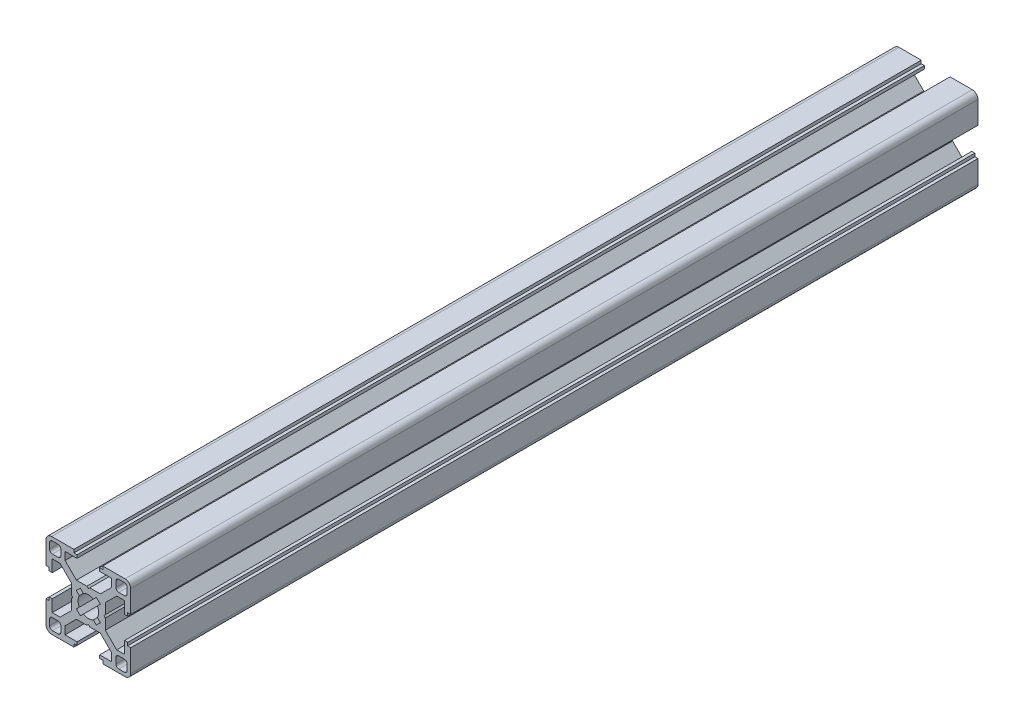
SolidWorks part; units mm, degrees
material "1060 Alloy"
ref_plane "Front Plane" through (0, 0, 0) normal (0, 0, 1) x (1, 0, 0)
ref_plane "Top Plane" through (0, 0, 0) normal (0, 1, 0) x (1, 0, 0)
ref_plane "Right Plane" through (0, 0, 0) normal (1, 0, 0) x (0, 0, -1)
sketch "Sketch1" plane through (0, 0, 0) normal (0, 0, 1) x (1, 0, 0)
  line L0 (5.1, 15) -> (13, 15)
  line L1 (15, -15) -> (-15, -15) construction
  line L2 (15, -15) -> (15, 15) construction
  line L3 (15, 15) -> (-15, 15) construction
  line L4 (-15, -15) -> (-15, 15) construction
  line L5 (15, -15) -> (-15, 15) construction
  line L6 (15, 15) -> (-15, -15) construction
  line L7 (-6, -6) -> (6, -6)
  line L8 (-6, -6) -> (-6, 6)
  line L9 (-6, 6) -> (4.2322, 6)
  line L10 (6, -6) -> (6, 4.2322)
  line L11 (-6, -6) -> (5.7915, 5.7915) construction
  line L12 (-6, 6) -> (6, -6) construction
  line L13 (15, 13) -> (15, 5.1)
  line L14 (15, 5.1) -> (13.9, 5.1)
  line L15 (13.9, 5.1) -> (13.9, 4)
  line L16 (13.9, 4) -> (12.8, 4)
  line L17 (12.8, 4) -> (12.8, 8.25)
  line L18 (12.8, 8.25) -> (10.0178, 8.25)
  line L19 (10.0178, 8.25) -> (6, 4.2322)
  line L20 (5.1, 15) -> (5.1, 13.9)
  line L21 (5.1, 13.9) -> (4, 13.9)
  line L22 (4, 13.9) -> (4, 12.8)
  line L23 (4, 12.8) -> (8.25, 12.8)
  line L24 (8.25, 12.8) -> (8.25, 10.0178)
  line L25 (8.25, 10.0178) -> (4.2322, 6)
  line L26 (4.2322, 6) -> (6, 4.2322) construction
  line L28 (13.75, 9.75) -> (9.75, 9.75)
  line L29 (13.75, 9.75) -> (13.75, 13.75)
  line L30 (13.75, 13.75) -> (9.75, 13.75)
  line L31 (9.75, 9.75) -> (9.75, 13.75)
  line L32 (13.75, 9.75) -> (9.75, 13.75) construction
  line L33 (13.75, 13.75) -> (9.75, 9.75) construction
  circle A0 centre (0, 0) radius 3.65
  arc A1 (15, 13) -> (13, 15) centre (13, 13) ccw
  point P12 (11.75, 11.75)
  dimension "D1" = 7.3
  dimension "D9" = 2
  dimension "D10" = 4
  dimension "D2" = 30
  dimension "D3" = 9
  dimension "D4" = 6.8
  dimension "D5" = 5.1
  dimension "D6" = 4
  dimension "D7" = 8.25
  dimension "D8" = 2.5
  dimension "D11" = 1.5
extrude "Boss-Extrude1" add sketch "Sketch1" along normal blind 300
fillet "Fillet1" radius 1 4 edges at (13.75, 9.75, 150) (13.75, 13.75, 150) (9.75, 13.75, 150) (9.75, 9.75, 150)
pattern_circular "CirPattern1" count 4 over 360 about axis through (0, 0, 0) along (0, 0, 1) of "Boss-Extrude1", "Fillet1"
sketch "Sketch2" plane through (0, 0, 0) normal (0, 0, -1) x (-1, 0, 0)
  line L0 (0, 5.5) -> (-0.5, 6)
  line L1 (-4.2322, 6) -> (4.2322, 6) construction
  line L2 (-0.5, 6) -> (0.5, 6)
  line L3 (0.5, 6) -> (0, 5.5)
  point P4 (0, 6)
  dimension "D1" = 0.5
extrude "Cut-Extrude1" cut sketch "Sketch2" against normal through all
sketch "Sketch3" plane through (0, 0, 0) normal (0, 0, -1) x (-1, 0, 0)
  line L0 (-1.7751, 3.1893) -> (-2.8284, 4.2426)
  line L1 (-2.8284, 4.2426) -> (-4.2426, 2.8284)
  line L2 (-4.2426, 2.8284) -> (-3.1893, 1.7751)
  line L3 (-3.5355, 3.5355) -> (0, 0) construction
  line L4 (-6, 4.2322) -> (-10.0178, 8.25) construction
  circle A0 centre (0, 0) radius 3.65 construction
  arc A1 (-3.1893, 1.7751) -> (-1.7751, 3.1893) centre (0, 0) cw
  dimension "D1" = 2
  dimension "D2" = 5
extrude "Cut-Extrude2" cut sketch "Sketch3" against normal through all
pattern_circular "CirPattern2" count 4 over 360 about axis through (0, 0, 0) along (0, 0, 1) of "Cut-Extrude1", "Cut-Extrude2"
